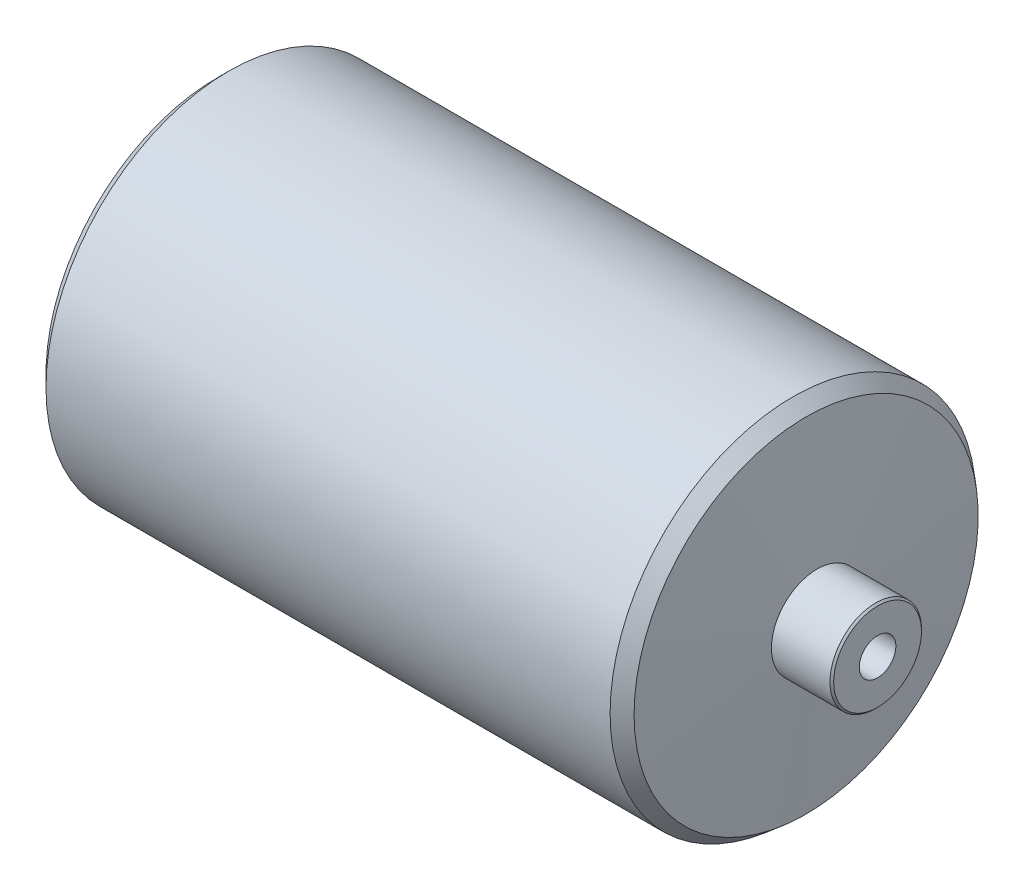
SolidWorks part; units mm, degrees
ref_plane "Alzado" through (0, 0, 0) normal (0, 0, 1) x (1, 0, 0)
ref_plane "Planta" through (0, 0, 0) normal (0, 1, 0) x (1, 0, 0)
ref_plane "Vista lateral" through (0, 0, 0) normal (1, 0, 0) x (0, 0, -1)
sketch "Croquis1" plane through (0, 0, 0) normal (0, 0, 1) x (1, 0, 0)
  line L0 (98, 5) -> (157, 5)
  line L1 (157, 5) -> (157, 0)
  line L2 (157, 0) -> (239, 0)
  line L3 (239, 0) -> (239, 5)
  line L4 (239, 5) -> (298, 5)
  line L5 (298, 5) -> (298, 12.5)
  line L6 (298, 12.5) -> (281.5, 12.5)
  line L7 (281.5, 12.5) -> (278.2192, 50)
  line L8 (278.2192, 50) -> (117.7808, 50)
  line L9 (117.7808, 50) -> (114.5, 12.5)
  line L10 (114.5, 12.5) -> (98, 12.5)
  line L11 (98, 12.5) -> (98, 5)
  line L12 (98, 5) -> (98.3996, 5)
  line L13 (26.6369, 0) -> (386.5111, 0) construction
  point P2 (98, 8.75)
  dimension "D1" = 7.5
  dimension "D2" = 85
  dimension "D3" = 85
  dimension "D4" = 200
  dimension "D5" = 59
  dimension "D6" = 59
  dimension "D7" = 5
  dimension "D8" = 5
  dimension "D9" = 16.5
  dimension "D10" = 16.5
  dimension "D11" = 7.5
  dimension "D12" = 50
revolve "Revolución1" add sketch "Croquis1" angle 360 about L13
chamfer "Chaflán1" distance 3 angle 45 2 edges at (117.7808, 0, 50) (278.2192, 0, 50)
chamfer "Chaflán2" distance 0.5 angle 45 2 edges at (298, 0, 12.5) (98, 0, 12.5)
